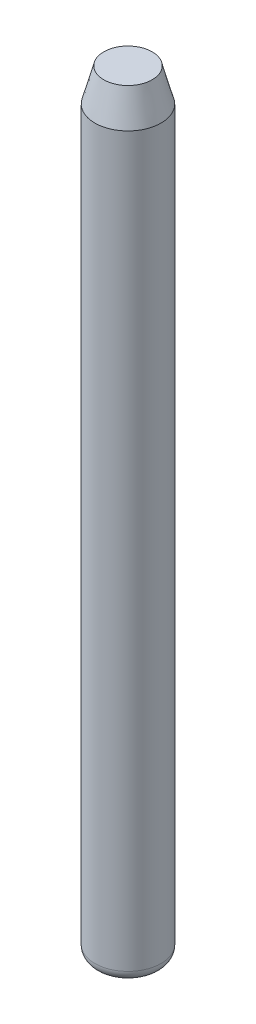
SolidWorks part; units mm, degrees
ref_plane "Front Plane" through (0, 0, 0) normal (0, 0, 1) x (1, 0, 0)
ref_plane "Top Plane" through (0, 0, 0) normal (0, 1, 0) x (1, 0, 0)
ref_plane "Right Plane" through (0, 0, 0) normal (1, 0, 0) x (0, 0, -1)
sketch "Sketch1" plane through (0, 0, 0) normal (0, 1, 0) x (1, 0, 0)
  circle A0 centre (0, 0) radius 1.5
  dimension "D1" = 3
extrude "Boss-Extrude1" add sketch "Sketch1" along normal blind 35
chamfer "Chamfer1" distance 1.5 angle 15 1 edges at (0, 35, 1.5)
fillet "Fillet1" radius 0.5 1 edges at (0, 0, 1.5)
